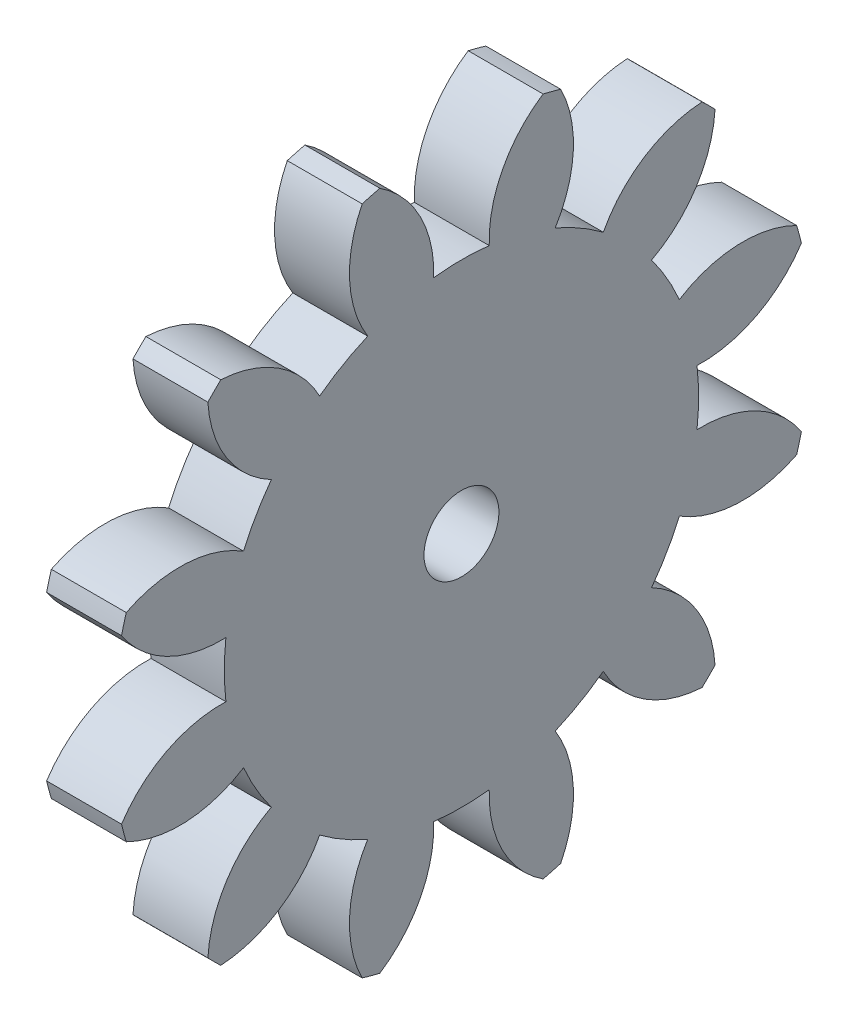
SolidWorks part; units mm, degrees
ref_plane "Plane1" through (0, 0, 0) normal (0, 0, 1) x (1, 0, 0)
ref_plane "Plane2" through (0, 0, 0) normal (0, 1, 0) x (1, 0, 0)
ref_plane "Plane3" through (0, 0, 0) normal (1, 0, 0) x (0, 0, -1)
sketch "HoldingSke" plane through (0, 0, 0) normal (0, 1, 0) x (1, 0, 0)
  line L0 (0, 0) -> (0.4891, -0.104)
  line L1 (-15, 0) -> (100, 0) construction
  line L2 (0, 0) -> (-2.1039, 2.3779)
  line L3 (0, 0) -> (-11.863, 4.5341)
  line L4 (0, 0) -> (8.4473, 1.7955)
  line L5 (0, 0) -> (-46.8476, -17.4728)
  line L6 (0, 0) -> (-2.4869, -1.6779)
  line L7 (-2.1039, 2.3779) -> (8.6586, 51.2059)
  line L8 (-76.2, 54.61) -> (-75.7, 54.61)
  line L9 (-71.009, 38.7566) -> (-53.1078, 45.2721)
  line L10 (-76.2, 71.12) -> (104.1128, 71.12)
  line L11 (0, 0) -> (-3, 0)
  line L12 (-76.2, 101.6) -> (-76.133, 101.6)
  line L13 (24.9733, 27.94) -> (52.9518, 28.4284)
  line L14 (24.9733, 27.94) -> (24.9743, 27.94)
  line L15 (24.9733, 27.94) -> (100.4006, 29.5858)
  line L16 (-63.627, -2) -> (-12.827, -2)
  circle A0 centre (0, 0) radius 1.5
  circle A1 centre (0, 0) radius 9.499
  circle A2 centre (0, 0) radius 37.5
  circle A3 centre (0, 0) radius 1.5
  dimension "MHD" = 18.998
  dimension "Hub_dia" = 75
  dimension "Bore" = 3
  dimension "MBD" = 3
  dimension "Num_teeth" = 12
  dimension "Pitch" = 0.5
  dimension "Overall_len" = 50
  dimension "Show_teeth" = 12
  dimension "Thickness" = 3
  dimension "OAL" = 50.0001
  dimension "T_dim" = 0.5
  dimension "Ap" = 20
  dimension "H" = 19.05
  dimension "Pitch_radius" = 180.3128
  dimension "Width" = 3
  dimension "Backlash" = 0.067
  dimension "Addendum_fac" = 1
  dimension "Dedendum_fac" = 1.25
  dimension "Clearance_fac" = 0.25
  dimension "Dedendum_add" = 0.001
  dimension "Module" = 2
sketch "BasProSke" plane through (0, 0, 0) normal (0, 1, 0) x (1, 0, 0)
  line L0 (-10, 0) -> (60, 0) construction
  line L1 (0, 0) -> (0, 14)
  line L2 (0, 0) -> (3, 0)
  line L3 (3, 0) -> (3, 14)
  line L4 (3, 14) -> (0, 14)
  dimension "Thickness" = 3
  dimension "Diameter" = 28
revolve "Base-Revolve" add sketch "BasProSke" angle 360 about L0
sketch "TooCutSke" plane through (0, 0, 0) normal (1, 0, 0) x (0, 0, -1)
  line L1 (0, 0) -> (0, 107) construction
  line L2 (0, 0) -> (-1.6834, 11.8813) construction
  line L3 (0, 0) -> (-6.1662, 23.0126) construction
  line L4 (-1.6834, 11.8813) -> (-3.0831, 11.5063) construction
  arc A0 (1.1119, 9.4337) -> (-1.1119, 9.4337) centre (0, 0) ccw
  arc A1 (3.2981, 13.6321) -> (-3.2981, 13.6321) centre (0, 0) ccw
  circle A2 centre (0, 0) radius 12 construction
  circle A3 centre (0, 0) radius 11.2763 construction
  arc A4 (-1.1119, 9.4337) -> (-3.2981, 13.6321) centre (-5.9089, 9.6042) ccw
  arc A5 (3.2981, 13.6321) -> (1.1119, 9.4337) centre (5.9089, 9.6042) ccw
  dimension "Root_dia" = 18.998
  dimension "Overcut_dia" = 28.0508
  dimension "Pitch_dia" = 24
  dimension "Base_dia" = 22.5526
  dimension "Flank_rad" = 4.8
  dimension "Half_ang" = 15
  dimension "Half_CT" = 1.4491
extrude "ToothCut" cut sketch "TooCutSke" along normal through all
fillet "Breaks" [suppressed] radius 0.04
fillet "RootFillets" [suppressed] radius 0.501
pattern_circular "TeethCuts" count 12 over 360 about axis through (0, 0, 0) along (1, 0, 0) of "ToothCut", "RootFillets", "Breaks"
sketch "HubNeaOneSke" plane through (0, 0, 0) normal (-1, 0, 0) x (0, 0, 1)
  circle A0 centre (0, 0) radius 9.499
  dimension "Diameter" = 18.998
extrude "HubNearOne" [suppressed] add sketch "HubNeaOneSke" along normal blind 47.0001
sketch "HubNeaBotSke" plane through (0, 0, 0) normal (-1, 0, 0) x (0, 0, 1)
  circle A0 centre (0, 0) radius 9.499
  dimension "Diameter" = 18.998
extrude "HubNearBoth" [suppressed] add sketch "HubNeaBotSke" along normal blind 23.5
ref_plane "FarPln" through (3, 0, 0) normal (1, 0, 0) x (0, 0, -1)
sketch "HubFarSke" plane through (3, 0, 0) normal (1, 0, 0) x (0, 0, -1)
  circle A0 centre (0, 0) radius 9.499
  dimension "Diameter" = 18.998
extrude "HubFar" [suppressed] add sketch "HubFarSke" along normal blind 23.5
sketch "BorSke" plane through (0, 0, 0) normal (1, 0, 0) x (0, 0, -1)
  circle A0 centre (0, 0) radius 1.5
  dimension "Diameter" = 3
extrude "Bore" cut sketch "BorSke" along normal mid plane 100.0001
sketch "KeySke" plane through (0, 0, 0) normal (1, 0, 0) x (0, 0, -1)
  line L0 (-0.6, 0) -> (-0.6, 2)
  line L1 (-0.6, 2) -> (0.6, 2)
  line L2 (0.6, 2) -> (0.6, 0)
  line L3 (0, 0) -> (0, 34) construction
  line L4 (-0.6, 0) -> (0.6, 0)
  dimension "Offset" = 2
  dimension "Width" = 1.2
extrude "Keyway" [suppressed] cut sketch "KeySke" along normal mid plane 100.0001
pattern_circular "Keyway2" [suppressed] count 2 every 90 about axis through (-10, 0, 0) along (1, 0, 0)
equation "' \"Module@HoldingSke\" = 6.35"
equation "' \"Num_teeth@HoldingSke\" = 12"
equation "' \"Ap@HoldingSke\" =  20"
equation "' \"Ap@HoldingSke\" = 20"
equation "' \"Width@HoldingSke\" = 0.5 * 25.4"
equation "' \"Hub_dia@HoldingSke\"= 1 * 25.4"
equation "' \"Hub_dia@HoldingSke\" = 1 * 25.4"
equation "' \"Overall_len@HoldingSke\" = 1.0 * 25.4"
equation "' \"Bore@HoldingSke\" = 0.75 * 25.4"
equation "' \"T_dim@HoldingSke\" = 0.1 * 25.4"
equation "' \"Width@KeySke\" = 0.25 * 25.4"
equation "' \"Show_teeth@HoldingSke\" = 13"
equation "' \"Backlash@HoldingSke\" = 0.009 * 25.4"
equation "' \"Addendum_fac@HoldingSke\" = 1.0"
equation "' \"Dedendum_fac@HoldingSke\" = 1.25"
equation "' \"Dedendum_add@HoldingSke\" = 0.00005 * 25.4"
equation "' \"Clearance_fac@HoldingSke\" = 0.25"
equation "\"Pitch@HoldingSke\" = 1 / \"Module@HoldingSke\""
equation "\"Overcut_dia@TooCutSke\" = (\"Num_teeth@HoldingSke\" + 2 * \"Addendum_fac@HoldingSke\") / \"Pitch@HoldingSke\" + 0.002 * 25.4"
equation "\"Pitch_dia@TooCutSke\" = \"Num_teeth@HoldingSke\" / \"Pitch@HoldingSke\""
equation "\"Base_dia@TooCutSke\" = \"Num_teeth@HoldingSke\" / \"Pitch@HoldingSke\" * cos((\"Ap@HoldingSke\"  * 3.14159265 / 180))"
equation "\"Root_dia@TooCutSke\" = (\"Num_teeth@HoldingSke\" + 2) / \"Pitch@HoldingSke\" - 2 * (\"Addendum_fac@HoldingSke\" + \"Dedendum_fac@HoldingSke\") / \"Pitch@HoldingSke\" - \"Dedendum_add@HoldingSke\" * 2"
equation "\"Half_ang@TooCutSke\" = 180 / \"Num_teeth@HoldingSke\""
equation "\"Half_CT@TooCutSke\" = \"Num_teeth@HoldingSke\" / \"Pitch@HoldingSke\" * sin((3.14159265 / 2 / \"Num_teeth@HoldingSke\")) / 2 - 7 * \"Backlash@HoldingSke\" / 4"
equation "\"Flank_rad@TooCutSke\" = \"Num_teeth@HoldingSke\" / \"Pitch@HoldingSke\" / 5"
equation "\"Radius@RootFillets\" = \"Clearance_fac@HoldingSke\" / \"Pitch@HoldingSke\" + \"Dedendum_add@HoldingSke\""
equation "\"Break_rad@Breaks\" = 0.02 / \"Pitch@HoldingSke\""
equation "\"Thickness@HoldingSke\" = \"Width@HoldingSke\""
equation "\"OAL@HoldingSke\" = \"Thickness@HoldingSke\""
equation "\"MHD@HoldingSke\" = (\"Num_teeth@HoldingSke\" + 2) / \"Pitch@HoldingSke\" - 2 * (\"Addendum_fac@HoldingSke\" + \"Dedendum_fac@HoldingSke\")  / \"Pitch@HoldingSke\" - \"Dedendum_add@HoldingSke\" * 2"
equation "\"MBD@HoldingSke\" = (\"Num_teeth@HoldingSke\" + 2) / \"Pitch@HoldingSke\" - 2 * (\"Addendum_fac@HoldingSke\" + \"Dedendum_fac@HoldingSke\")  / \"Pitch@HoldingSke\" - \"Dedendum_add@HoldingSke\" * 2 - 0.002 * 25.4"
equation "\"MHD@HoldingSke\" = ((sgn( \"MHD@HoldingSke\" - \"Hub_dia@HoldingSke\" )-1)*( \"MHD@HoldingSke\" - \"Hub_dia@HoldingSke\" ))/-2+ \"Hub_dia@HoldingSke\""
equation "\"MBD@HoldingSke\" = ((sgn( \"MBD@HoldingSke\" - \"Bore@HoldingSke\" )-1)*( \"MBD@HoldingSke\" - \"Bore@HoldingSke\" ))/-2+ \"Bore@HoldingSke\""
equation "\"OAL@HoldingSke\" = ((sgn( \"OAL@HoldingSke\" - \"Overall_len@HoldingSke\" )+1)*( \"OAL@HoldingSke\" - \"Overall_len@HoldingSke\" ))/2 + \"Overall_len@HoldingSke\" + 0.000002 * 25.4"
equation "\"Num_teeth@TeethCuts\" = int( \"Show_teeth@HoldingSke\" ) + 1"
equation "\"Num_teeth@TeethCuts\" = ((sgn( \"Num_teeth@TeethCuts\" - \"Num_teeth@HoldingSke\" )-1)*( \"Num_teeth@TeethCuts\" - \"Num_teeth@HoldingSke\" ))/-2+ \"Num_teeth@HoldingSke\""
equation "\"Num_teeth@TeethCuts\" = ((sgn( \"Num_teeth@TeethCuts\" - 2.0)+1)*( \"Num_teeth@TeethCuts\" - 2.0))/2 +2.0"
equation "\"Angle@TeethCuts\" = 360.0 / \"Num_teeth@HoldingSke\""
equation "\"Diameter@BasProSke\" = (\"Num_teeth@HoldingSke\" + 2 * \"Addendum_fac@HoldingSke\") / \"Pitch@HoldingSke\""
equation "\"Thickness@BasProSke\"  = \"Thickness@HoldingSke\""
equation "' \"Fillet_rad@BasProSke\" =  \"Thickness@HoldingSke\" * 0.05"
equation "' \"Fillet_rad@BasProSke\" = \"Thickness@HoldingSke\" * 0.05"
equation "\"MHD@HoldingSke\" = ((sgn( \"MHD@HoldingSke\" - \"Root_dia@TooCutSke\" )-1)*( \"MHD@HoldingSke\" - \"Root_dia@TooCutSke\" ))/-2+ \"Root_dia@TooCutSke\""
equation "\"Diameter@HubNeaOneSke\" = \"MHD@HoldingSke\""
equation "\"Length@HubNearOne\" = \"OAL@HoldingSke\" - \"Thickness@BasProSke\""
equation "\"Diameter@HubNeaBotSke\" = \"MHD@HoldingSke\""
equation "\"Length@HubNearBoth\" = ( \"OAL@HoldingSke\" - \"Thickness@BasProSke\" ) / 2.0"
equation "\"Thickness@FarPln\" = \"Thickness@BasProSke\""
equation "\"Diameter@HubFarSke\" = \"MHD@HoldingSke\""
equation "\"Length@HubFar\" = ( \"OAL@HoldingSke\" - \"Thickness@BasProSke\" ) / 2.0"
equation "\"Diameter@BorSke\" = \"MBD@HoldingSke\""
equation "\"D1@Bore\" = \"OAL@HoldingSke\" * 2.0"
equation "\"D1@Keyway\" = \"OAL@HoldingSke\" * 2.0"
equation "\"Offset@KeySke\" = \"T_dim@HoldingSke\" + \"MBD@HoldingSke\" / 2.0"
